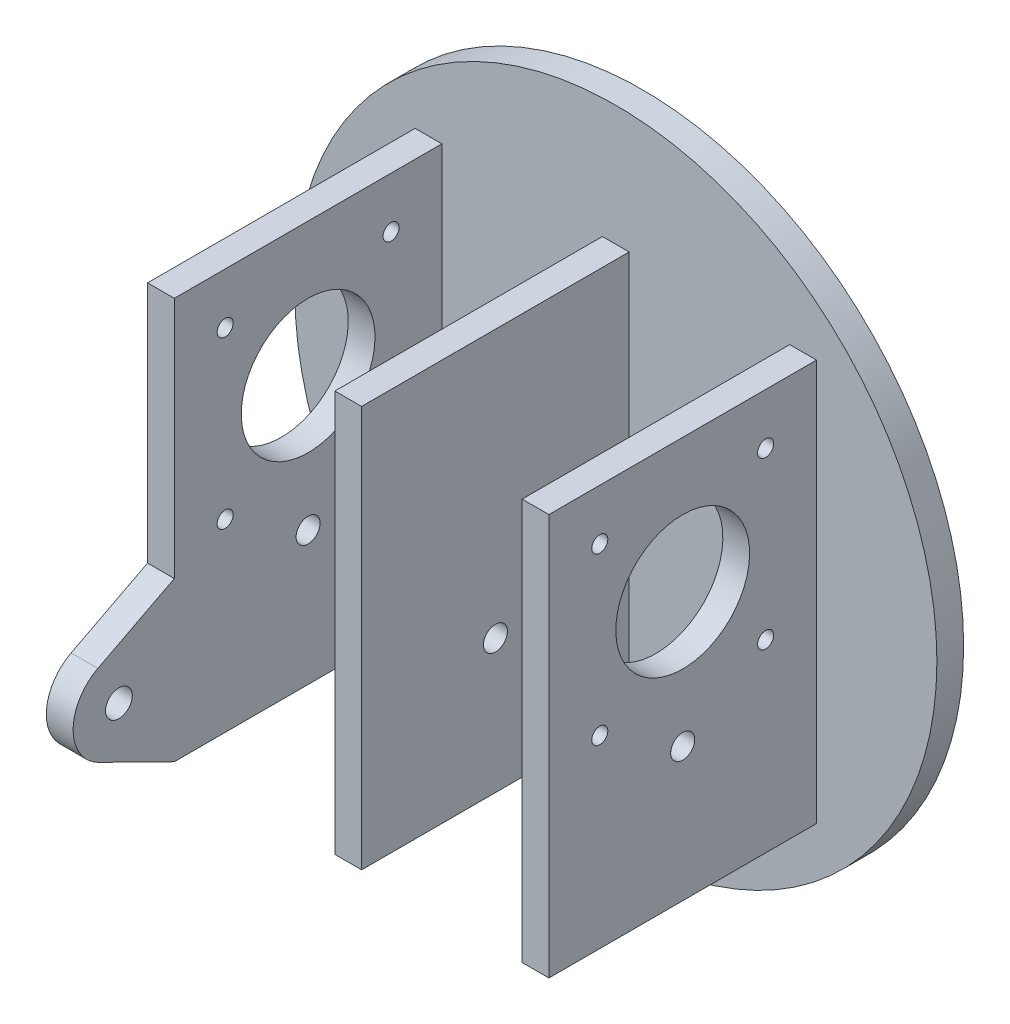
SolidWorks part; units mm, degrees
ref_plane "Front Plane" through (0, 0, 0) normal (0, 0, 1) x (1, 0, 0)
ref_plane "Top Plane" through (0, 0, 0) normal (0, 1, 0) x (1, 0, 0)
ref_plane "Right Plane" through (0, 0, 0) normal (1, 0, 0) x (0, 0, -1)
sketch "Sketch1" plane through (0, 0, 0) normal (0, 0, 1) x (1, 0, 0)
  circle A0 centre (0, 0) radius 60
  circle A1 centre (0, 0) radius 1.5
  dimension "D1" = 120
  dimension "D2" = 3
extrude "Boss-Extrude1" add sketch "Sketch1" along normal blind 5
sketch "Sketch2" plane through (0, 0, 0) normal (0, 0, -1) x (-1, 0, 0)
  line L0 (37.5, 37.5) -> (-37.5, -37.5) construction
  line L1 (-37.5, 37.5) -> (37.5, -37.5) construction
  line L3 (-37.5, 37.5) -> (-32.5, 37.5)
  line L4 (-37.5, 37.5) -> (-37.5, -37.5)
  line L5 (-37.5, -37.5) -> (-32.5, -37.5)
  line L6 (-32.5, 37.5) -> (-32.5, -37.5)
  line L7 (37.5, 37.5) -> (32.5, 37.5)
  line L8 (37.5, 37.5) -> (37.5, -37.5)
  line L9 (37.5, -37.5) -> (32.5, -37.5)
  line L10 (32.5, 37.5) -> (32.5, -37.5)
  line L11 (-2.5, -37.5) -> (2.5, -37.5)
  line L12 (-2.5, -37.5) -> (-2.5, 37.5)
  line L13 (-2.5, 37.5) -> (2.5, 37.5)
  line L14 (2.5, -37.5) -> (2.5, 37.5)
  line L15 (-2.5, -37.5) -> (2.5, 37.5) construction
  line L16 (-2.5, 37.5) -> (2.5, -37.5) construction
  point P7 (0, 0)
  dimension "D1" = 75
  dimension "D2" = 5
extrude "Boss-Extrude2" add sketch "Sketch2" along normal blind 50
sketch "Sketch3" plane through (32.5, 0, 0) normal (-1, 0, 0) x (0, 0, 1)
  line L0 (-50, -37.5) -> (0, 12.5) construction
  line L1 (-50, -37.5) -> (-50, 37.5) construction
  line L2 (-50, -37.5) -> (0, -37.5) construction
  line L3 (0, -37.5) -> (0, 37.5) construction
  line L4 (0, -37.5) -> (-50, 12.5) construction
  circle A0 centre (-40.5, 3) radius 1.5
  circle A1 centre (-9.5, 3) radius 1.5
  circle A2 centre (-9.5, -28) radius 1.5
  circle A3 centre (-40.5, -28) radius 1.5
  circle A4 centre (-25, -12.5) radius 12.5
  dimension "D2" = 3
  dimension "D4" = 25
  dimension "D1" = 45
  dimension "D3" = 31
extrude "Cut-Extrude1" cut sketch "Sketch3" against normal through all
sketch "Sketch5" plane through (-2.5, 0, 0) normal (-1, 0, 0) x (0, 0, 1)
  line L0 (-25, -37.5) -> (-25, 37.5) construction
  line L1 (-50, -37.5) -> (0, -37.5) construction
  line L2 (-50, 37.5) -> (0, 37.5) construction
  line L4 (-23.4125, -14.0875) -> (-26.5875, -14.0875)
  line L5 (-23.4125, -14.0875) -> (-23.4125, -10.9125)
  line L6 (-23.4125, -10.9125) -> (-26.5875, -10.9125)
  line L7 (-26.5875, -14.0875) -> (-26.5875, -10.9125)
  line L8 (-23.4125, -14.0875) -> (-26.5875, -10.9125) construction
  line L9 (-23.4125, -10.9125) -> (-26.5875, -14.0875) construction
  circle A0 centre (-25, -12.5) radius 2.2451
  circle A1 centre (-25, 12.5) radius 2.2451
  dimension "D3" = 3.175
  dimension "D1" = 25
  dimension "D2" = 25
extrude "Cut-Extrude4" cut sketch "Sketch5" against normal blind 53 and the other way through all contours A1
sketch "Sketch6" plane through (-37.5, 0, 0) normal (-1, 0, 0) x (0, 0, 1)
  line L0 (-50, -37.5) -> (0, 12.5) construction
  line L1 (0, -37.5) -> (-50, 12.5) construction
  circle A0 centre (-40.5, 3) radius 1.5
  circle A1 centre (-9.5, 3) radius 1.5
  circle A2 centre (-9.5, -28) radius 1.5
  circle A3 centre (-40.5, -28) radius 1.5
  circle A4 centre (-25, -12.5) radius 12.5
  dimension "D1" = 3
  dimension "D3" = 25
  dimension "D2" = 31
extrude "Cut-Extrude5" cut sketch "Sketch6" against normal up to surface (5 mm away) up to face at (-32.5, 10.2549, -25)
sketch "Sketch7" plane through (-37.5, 0, 0) normal (-1, 0, 0) x (0, 0, 1)
  line L0 (-25, -12.5) -> (-60.3553, 22.8553) construction
  line L1 (0, 60) -> (0, -60) construction
  line L2 (-50, 37.5) -> (-64.1385, 30.5347)
  line L3 (-64.2907, 15.2528) -> (-50, 7.8553)
  line L4 (-50, -37.5) -> (-50, 37.5) construction
  line L6 (-50, 7.8553) -> (-50, 37.5)
  circle A2 centre (-25, -12.5) radius 12.5 construction
  circle A3 centre (-60.3553, 22.8553) radius 2.5
  arc A4 (-64.2907, 15.2528) -> (-64.1385, 30.5347) centre (-60.3553, 22.8553) cw
  dimension "D3" = 5
  dimension "D1" = 50
  dimension "D2" = 45
  dimension "D4" = 15
extrude "Boss-Extrude4" add sketch "Sketch7" against normal blind 5
move or copy body "Body-Move/Copy1" bodies to move or copy 109 copy no rotation origin (0, 0, -31.958) rotation axis (1, 0, 0) rotation angle 180
move or copy body "Body-Move/Copy2" bodies to move or copy 110 copy no translate (0, 0, 68.916)
